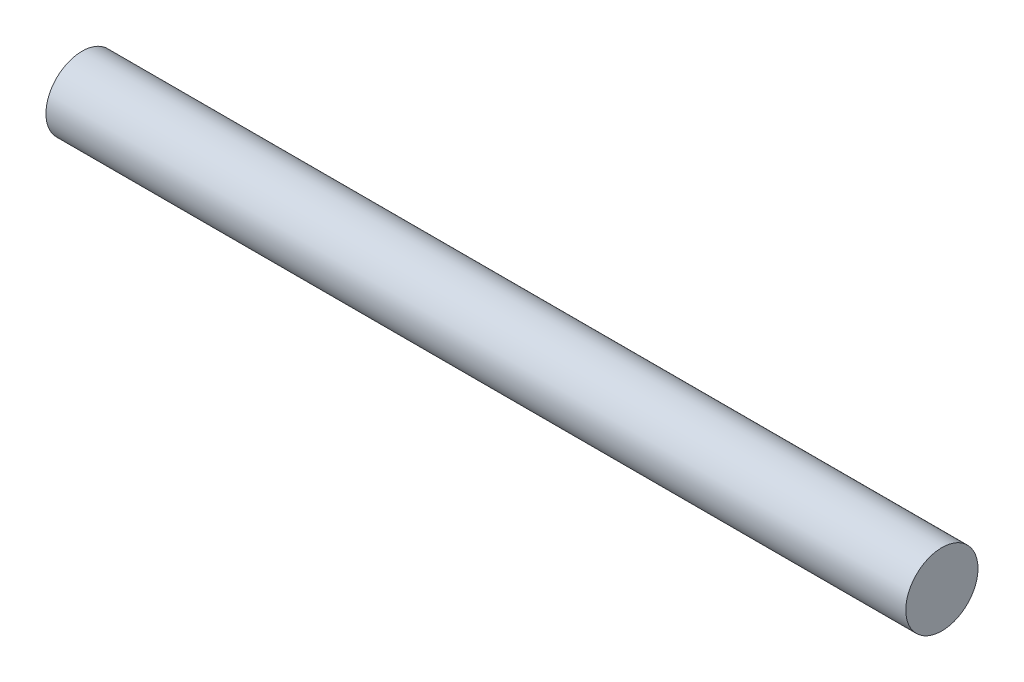
SolidWorks part; units mm, degrees
ref_plane "Alzado" through (0, 0, 0) normal (0, 0, 1) x (1, 0, 0)
ref_plane "Planta" through (0, 0, 0) normal (0, 1, 0) x (1, 0, 0)
ref_plane "Vista lateral" through (0, 0, 0) normal (1, 0, 0) x (0, 0, -1)
sketch "Croquis1" plane through (0, 0, 0) normal (1, 0, 0) x (0, 0, -1)
  circle A0 centre (0, 0) radius 84
  circle A1 centre (0, 0) radius 79
  dimension "D1" = 158
  dimension "D2" = 168
extrude "Saliente-Extruir1" add sketch "Croquis1" along normal blind 2000
sketch "Croquis2" plane through (0, 0, 0) normal (-1, 0, 0) x (0, 0, 1)
  circle A0 centre (0, 0) radius 84
  circle A1 centre (0, 0) radius 84 construction
  dimension "D1" = 168
extrude "Saliente-Extruir2" add sketch "Croquis2" against normal blind 10
sketch "Croquis3" plane through (2000, 0, 0) normal (1, 0, 0) x (0, 0, -1)
  circle A0 centre (0, 0) radius 84
  circle A1 centre (0, 0) radius 84 construction
  dimension "D1" = 168
extrude "Saliente-Extruir3" add sketch "Croquis3" against normal blind 10
